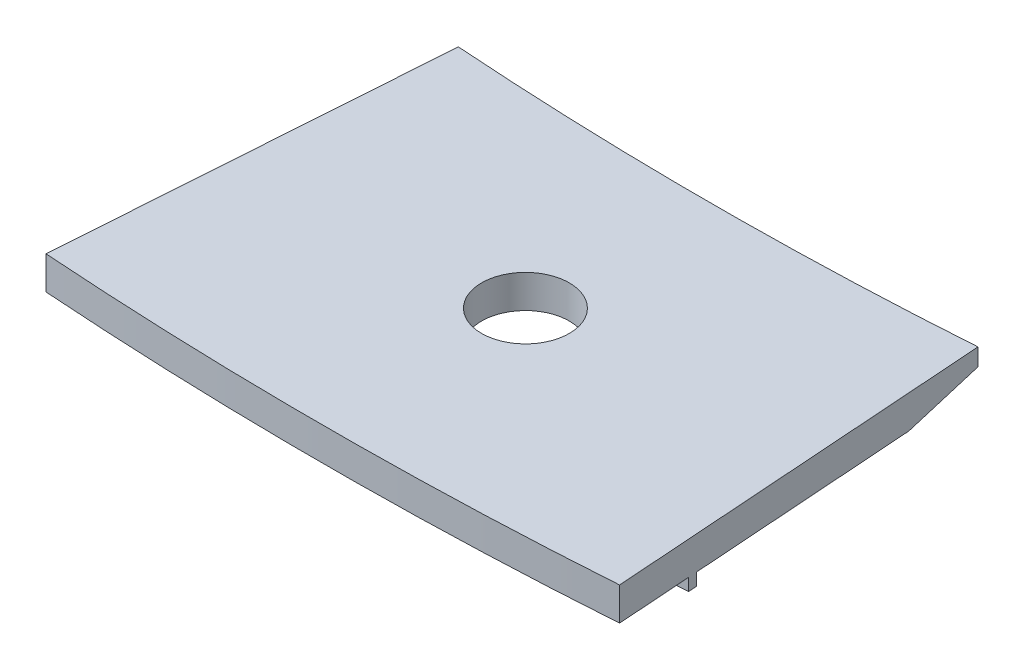
SolidWorks part; units mm, degrees
ref_plane "Front Plane" through (0, 0, 0) normal (0, 0, 1) x (1, 0, 0)
ref_plane "Top Plane" through (0, 0, 0) normal (0, 1, 0) x (1, 0, 0)
ref_plane "Right Plane" through (0, 0, 0) normal (1, 0, 0) x (0, 0, -1)
sketch "BASE" plane through (0, 0, 0) normal (0, 1, 0) x (1, 0, 0)
  line L0 (0, 0) -> (0, -243.5) construction
  line L1 (15.9742, -228.4422) -> (16.9857, -242.9068)
  line L2 (-15.9742, -228.4422) -> (-16.9857, -242.9068)
  line L3 (0, 0) -> (15.9742, -228.4422) construction
  line L4 (0, 0) -> (-15.9742, -228.4422) construction
  line L5 (0, -229) -> (0, -243.5) construction
  line L7 (-10, -226.25) -> (10, -226.25) construction
  line L8 (-10, -226.25) -> (-10, -246.25) construction
  line L9 (-10, -246.25) -> (10, -246.25) construction
  line L10 (10, -226.25) -> (10, -246.25) construction
  line L11 (-10, -226.25) -> (10, -246.25) construction
  line L12 (-10, -246.25) -> (10, -226.25) construction
  arc A0 (-16.9857, -242.9068) -> (16.9857, -242.9068) centre (0, 0) ccw
  arc A1 (-15.9742, -228.4422) -> (15.9742, -228.4422) centre (0, 0) ccw
  circle A2 centre (0, -236.25) radius 2.65
  dimension "D1" = 487
  dimension "D2" = 14.5
  dimension "D6" = 5.3
  dimension "D3" = 4
  dimension "D4" = 4
  dimension "D5" = 20
sketch "Sketch2" plane through (0, 0, 0) normal (0, 1, 0) x (1, 0, 0)
  line L1 (-15.9742, -228.4422) -> (-16.9857, -242.9068) construction
  line L3 (15.9742, -228.4422) -> (16.9857, -242.9068) construction
  line L4 (0, 0) -> (-17.3345, -247.8947) construction
  line L5 (0, 0) -> (17.3345, -247.8947) construction
  line L6 (-15.9847, -228.5918) -> (-17.3345, -247.8947)
  line L7 (15.9847, -228.5918) -> (17.3345, -247.8947)
  arc A0 (15.9847, -228.5918) -> (-15.9847, -228.5918) centre (0, 0) cw
  arc A1 (-15.9742, -228.4422) -> (15.9742, -228.4422) centre (0, 0) ccw construction
  arc A2 (17.3345, -247.8947) -> (-17.3345, -247.8947) centre (0, 0) cw
  arc A3 (-16.9857, -242.9068) -> (16.9857, -242.9068) centre (0, 0) ccw construction
  circle A4 centre (0, -236.25) radius 2.65
  dimension "D1" = 0.15
  dimension "D2" = 5
  dimension "D3" = 5.3
extrude "Boss-Extrude1" add sketch "Sketch2" along normal blind 2
sketch "Sketch3" plane through (0, 0, 0) normal (0, 1, 0) x (1, 0, 0)
  line L0 (0, 0) -> (15.9742, -228.4422) construction
  line L1 (0, 0) -> (-15.9742, -228.4422) construction
  line L2 (-15.7057, -224.6015) -> (-15.9847, -228.5918)
  line L3 (15.7057, -224.6015) -> (15.9847, -228.5918)
  arc A0 (15.9847, -228.5918) -> (-15.9847, -228.5918) centre (0, 0) cw
  arc A1 (15.7057, -224.6015) -> (-15.7057, -224.6015) centre (0, 0) cw
  dimension "D1" = 4
extrude "Boss-Extrude2" add sketch "Sketch3" against normal blind 2 from surface at 2 starting at face at (0, 2, 238.5341)
chamfer "Chamfer1" distance 4.5 angle 12 1 edges at (0, 0, 225.15)
sketch "Sketch4" plane through (0, 0, 0) normal (0, -1, 0) x (1, 0, 0)
  line L0 (15.9742, 228.4422) -> (16.9857, 242.9068) construction
  line L1 (-16.0196, 229.0906) -> (-17.3345, 247.8947) construction
  line L2 (17.3345, 247.8947) -> (16.0196, 229.0906) construction
  line L3 (-17.0207, 243.4068) -> (-16.9857, 242.9068)
  line L4 (17.0207, 243.4068) -> (16.9857, 242.9068)
  arc A0 (-16.9857, 242.9068) -> (16.9857, 242.9068) centre (0, 0) cw
  arc A1 (-17.0207, 243.4068) -> (17.0207, 243.4068) centre (0, 0) cw
  dimension "D1" = 0.5
extrude "Boss-Extrude3" add sketch "Sketch4" along normal blind 0.75
